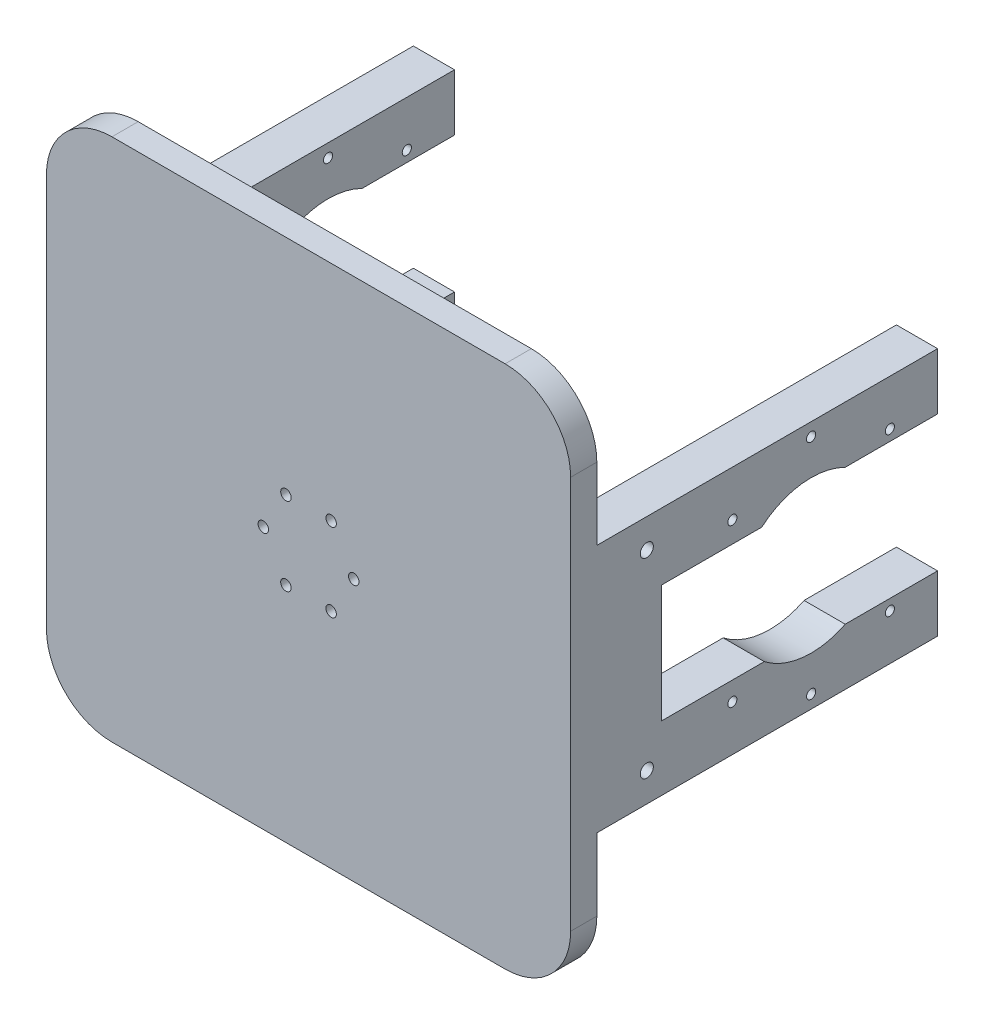
SolidWorks part; units mm, degrees
ref_plane "前视基准面" through (0, 0, 0) normal (0, 0, 1) x (1, 0, 0)
ref_plane "上视基准面" through (0, 0, 0) normal (0, 1, 0) x (1, 0, 0)
ref_plane "右视基准面" through (0, 0, 0) normal (1, 0, 0) x (0, 0, -1)
sketch "草图1" plane through (0, 0, 0) normal (0, 0, 1) x (1, 0, 0)
  line L1 (-100, 100) -> (100, 100)
  line L2 (-100, 100) -> (-100, -100)
  line L3 (-100, -100) -> (100, -100)
  line L4 (100, 100) -> (100, -100)
  line L5 (-100, 100) -> (100, -100) construction
  line L6 (-100, -100) -> (100, 100) construction
  point P0 (0, 0)
  dimension "D1" = 200
extrude "凸台-拉伸1" add sketch "草图1" along normal blind 10
sketch "草图2" plane through (0, 0, 0) normal (0, 0, -1) x (-1, 0, 0)
  line L0 (-84.3, 47.5) -> (-84.3, -47.5) construction
  line L1 (0, 0) -> (0, -99.8321) construction
  line L2 (84.3, 47.5) -> (84.3, -47.5) construction
  line L3 (-100, 0) -> (148.0086, 0) construction
  line L4 (-100, -100) -> (-100, 100) construction
  line L5 (100, 100) -> (100, -100) construction
  line L6 (-84.3, 47.5) -> (-100, 47.5)
  line L7 (-84.3, 47.5) -> (-84.3, -47.5)
  line L8 (-84.3, -47.5) -> (-100, -47.5)
  line L9 (-100, 47.5) -> (-100, -47.5)
  line L10 (84.3, 47.5) -> (100, 47.5)
  line L11 (84.3, 47.5) -> (84.3, -47.5)
  line L12 (84.3, -47.5) -> (100, -47.5)
  line L13 (100, 47.5) -> (100, -47.5)
  point P11 (-84.3, 0)
  dimension "D1" = 168.6
  dimension "D2" = 95
extrude "凸台-拉伸2" add sketch "草图2" along normal blind 130
sketch "草图3" plane through (-100, 0, 0) normal (-1, 0, 0) x (0, 0, 1)
  line L0 (-130, 0) -> (-33.5, 0) construction
  line L1 (-94.7668, 46.25) -> (-94.7668, -46.25) construction
  line L2 (-97.582, 46.25) -> (-61.658, 46.25)
  line L3 (-97.582, -46.25) -> (-61.658, -46.25)
  line L8 (0, 100) -> (0, 47.5)
  line L9 (0, 47.5) -> (-130, 47.5)
  line L10 (-130, 47.5) -> (-130, -47.5)
  line L11 (-130, -47.5) -> (0, -47.5)
  line L12 (0, -47.5) -> (0, -100)
  line L13 (0, -100) -> (10, -100)
  line L14 (10, -100) -> (10, 100)
  line L15 (10, 100) -> (0, 100)
  line L16 (0, 100) -> (0, 47.5)
  line L17 (0, 47.5) -> (-130, 47.5)
  line L18 (-130, 47.5) -> (-130, -47.5)
  line L19 (-130, -47.5) -> (0, -47.5)
  line L20 (0, -47.5) -> (0, -100)
  line L21 (0, -100) -> (10, -100)
  line L22 (10, -100) -> (10, 100)
  line L23 (10, 100) -> (0, 100)
  circle A0 centre (-81.75, 0) radius 48.25
  circle A1 centre (-81.75, 0) radius 42.5 construction
  circle A2 centre (-81.75, 42.5) radius 1.75
  circle A3 centre (-51.698, 30.052) radius 1.75
  circle A4 centre (-39.25, 0) radius 1.75
  circle A5 centre (-51.698, -30.052) radius 1.75
  circle A6 centre (-81.75, -42.5) radius 1.75
  circle A7 centre (-111.802, -30.052) radius 1.75
  circle A8 centre (-124.25, 0) radius 1.75
  circle A9 centre (-111.802, 30.052) radius 1.75
  point P10 (-94.7668, 0)
  point P40 (-81.75, 0)
  dimension "D4" = 85
  dimension "D5" = 3.5
  dimension "D2" = 92.5
  dimension "D3" = 96.5
  dimension "D6" = 8
  dimension "D1" = 0
extrude "切除-拉伸1" cut sketch "草图3" against normal through all contours A6 | A5 | A4 | A2 | A9 | A7 | A3 | A8
sketch "草图4" plane through (84.3, 0, 0) normal (-1, 0, 0) x (0, 0, 1)
  line L4 (0, -47.5) -> (0, 47.5)
  line L5 (0, 47.5) -> (-130, 47.5)
  line L6 (-130, 47.5) -> (-130, -47.5)
  line L7 (-130, -47.5) -> (0, -47.5)
  line L8 (0, -47.5) -> (0, 47.5)
  line L9 (0, 47.5) -> (-130, 47.5)
  line L10 (-130, 47.5) -> (-130, -47.5)
  line L11 (-130, -47.5) -> (0, -47.5)
  circle A0 centre (-111.802, 30.052) radius 1.75 construction
  circle A1 centre (-111.802, 30.052) radius 1.75
  circle A3 centre (-81.75, 0) radius 29
  dimension "D2" = 58
  dimension "D1" = 0
extrude "切除-拉伸2" cut sketch "草图4" against normal mid plane 1000 contours A3
sketch "草图5" plane through (100, 0, 0) normal (1, 0, 0) x (0, 0, -1)
  line L0 (111.802, 30.052) -> (81.2855, 30.052) construction
  line L1 (111.802, -30.052) -> (70.1595, -30.052) construction
  line L2 (113.2163, -25.9175) -> (81.2855, -25.9175) construction
  line L3 (83.4312, 0) -> (139.4584, 0) construction
  line L4 (130, 0) -> (33.5, 0) construction
  line L5 (113.2163, 25.9175) -> (81.2855, 25.9175) construction
  line L6 (51.698, 30.052) -> (51.698, 22.052) construction
  line L7 (81.2855, 25.9175) -> (132.8623, 25.9175)
  line L8 (81.2855, 25.9175) -> (81.2855, -25.9175)
  line L9 (81.2855, -25.9175) -> (132.8623, -25.9175)
  line L10 (132.8623, 25.9175) -> (132.8623, -25.9175)
  line L11 (51.698, -30.052) -> (51.698, -22.052) construction
  line L12 (24.5786, 22.052) -> (75.3686, 22.052) construction
  line L14 (75.3686, 22.052) -> (24.5786, 22.052)
  line L15 (75.3686, 22.052) -> (75.3686, -22.8492)
  line L16 (75.3686, -22.8492) -> (24.5786, -22.8492)
  line L17 (24.5786, 22.052) -> (24.5786, -22.8492)
  dimension "D1" = 8
extrude "切除-拉伸3" cut sketch "草图5" against normal through all
sketch "草图6" plane through (-100, 0, 0) normal (-1, 0, 0) x (0, 0, 1)
  line L0 (-81.75, 0) -> (0, -47.5) construction
  line L1 (-81.75, 0) -> (65.7617, 0) construction
  line L14 (-94.7609, -25.9175) -> (-130, -25.9175)
  line L15 (-130, -25.9175) -> (-130, -47.5)
  line L16 (-130, -47.5) -> (0, -47.5)
  line L17 (0, -47.5) -> (0, -100)
  line L18 (0, -100) -> (10, -100)
  line L19 (10, -100) -> (10, 100)
  line L20 (10, 100) -> (0, 100)
  line L21 (0, 100) -> (0, 47.5)
  line L22 (0, 47.5) -> (-130, 47.5)
  line L23 (-130, 47.5) -> (-130, 25.9175)
  line L24 (-130, 25.9175) -> (-94.7609, 25.9175)
  line L25 (-62.9163, 22.052) -> (-24.5786, 22.052)
  line L26 (-24.5786, 22.052) -> (-24.5786, -22.8492)
  line L27 (-24.5786, -22.8492) -> (-63.8918, -22.8492)
  line L28 (-94.7609, -25.9175) -> (-130, -25.9175)
  line L29 (-130, -25.9175) -> (-130, -47.5)
  line L30 (-130, -47.5) -> (0, -47.5)
  line L31 (0, -47.5) -> (0, -100)
  line L32 (0, -100) -> (10, -100)
  line L33 (10, -100) -> (10, 100)
  line L34 (10, 100) -> (0, 100)
  line L35 (0, 100) -> (0, 47.5)
  line L36 (0, 47.5) -> (-130, 47.5)
  line L37 (-130, 47.5) -> (-130, 25.9175)
  line L38 (-130, 25.9175) -> (-94.7609, 25.9175)
  line L39 (-62.9163, 22.052) -> (-24.5786, 22.052)
  line L40 (-24.5786, 22.052) -> (-24.5786, -22.8492)
  line L41 (-24.5786, -22.8492) -> (-63.8918, -22.8492)
  circle A0 centre (-81.75, 0) radius 60
  circle A1 centre (-19.0635, -36.4233) radius 12.5
  arc A2 (-94.7609, -25.9175) -> (-63.8918, -22.8492) centre (-81.75, 0) ccw
  arc A3 (-62.9163, 22.052) -> (-94.7609, 25.9175) centre (-81.75, 0) ccw
  arc A4 (-94.7609, -25.9175) -> (-63.8918, -22.8492) centre (-81.75, 0) ccw
  arc A5 (-62.9163, 22.052) -> (-94.7609, 25.9175) centre (-81.75, 0) ccw
  circle A6 centre (-19.0635, 36.4233) radius 12.5
  circle A7 centre (-19.0635, -36.4233) radius 2.5
  circle A8 centre (-19.0635, 36.4233) radius 2.5
  dimension "D2" = 120
  dimension "D3" = 25
  dimension "D4" = 5
  dimension "D1" = 0
extrude "切除-拉伸4" cut sketch "草图6" against normal through all contours A7 | A8
fillet "圆角1" radius 25 4 edges at (-100, -100, 5) (100, -100, 5) (100, 100, 5) (-100, 100, 5)
sketch "草图7" plane through (0, 0, 0) normal (0, 0, -1) x (-1, 0, 0)
  circle A0 centre (0, 0) radius 17.25 construction
  circle A1 centre (17.25, 0) radius 2
  circle A2 centre (8.625, -14.9389) radius 2
  circle A3 centre (-8.625, -14.9389) radius 2
  circle A4 centre (-17.25, 0) radius 2
  circle A5 centre (-8.625, 14.9389) radius 2
  circle A6 centre (8.625, 14.9389) radius 2
  point P18 (0, 0)
  dimension "D1" = 34.5
  dimension "D2" = 4
  dimension "D3" = 6
extrude "切除-拉伸5" cut sketch "草图7" against normal through all
